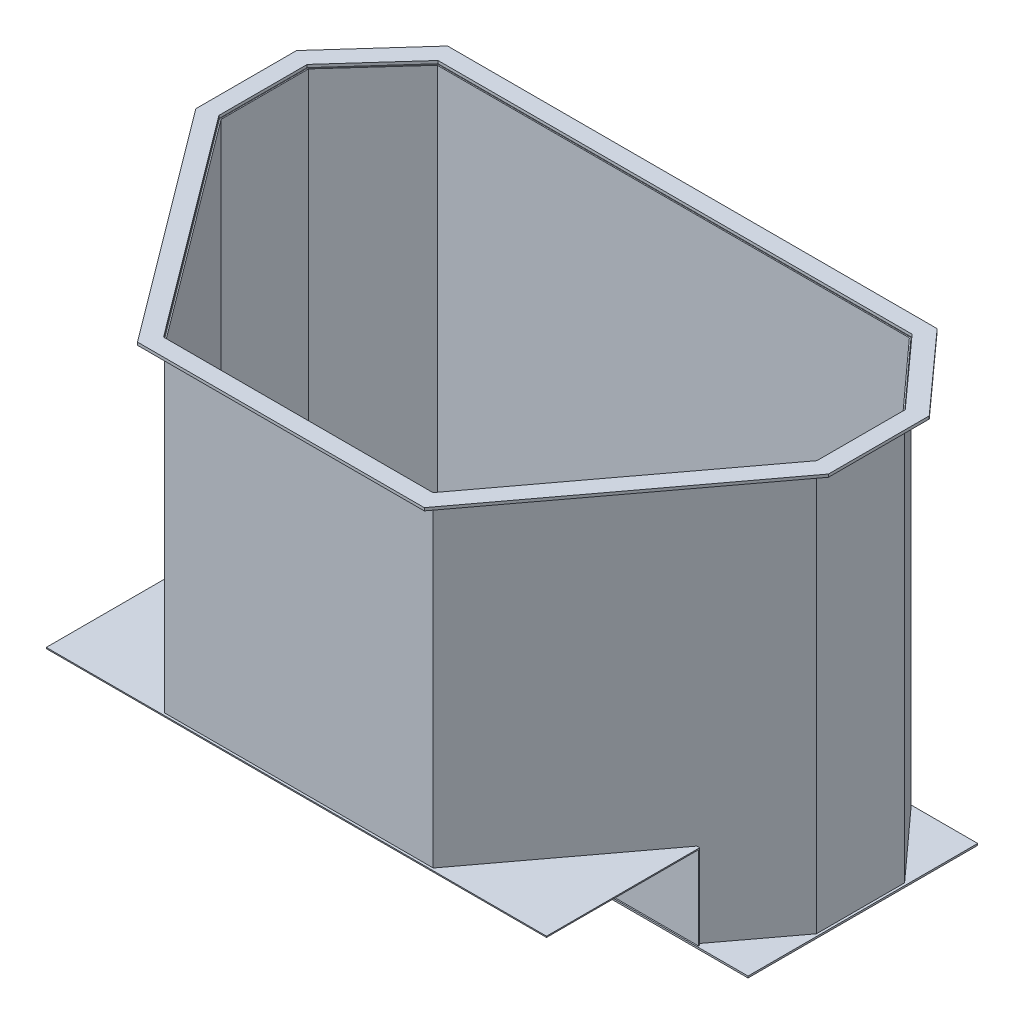
SolidWorks part; units mm, degrees
ref_plane "Front Plane" through (0, 0, 0) normal (0, 0, 1) x (1, 0, 0)
ref_plane "Top Plane" through (0, 0, 0) normal (0, 1, 0) x (1, 0, 0)
ref_plane "Right Plane" through (0, 0, 0) normal (1, 0, 0) x (0, 0, -1)
sketch "Sketch1" plane through (0, 0, 0) normal (0, 1, 0) x (1, 0, 0)
  line L0 (-5428.3271, 0) -> (7958.8254, 0) construction
  line L1 (0, -4061.0417) -> (0, 5407.9198) construction
  line L2 (-1675, 790) -> (1675, 790)
  line L3 (-950, -1860) -> (950, -1860)
  line L4 (-2110, 310) -> (-2110, -310)
  line L5 (2110, 310) -> (2110, -310)
  line L6 (-1661.4236, -790) -> (2260.7464, -790) construction
  line L7 (-1675, 790) -> (-2110, 310)
  line L8 (1675, 790) -> (2110, 310)
  line L9 (-950, -1860) -> (-2110, -310)
  line L10 (2110, -310) -> (950, -1860)
  line L11 (-1678.5464, 798) -> (1678.5464, 798)
  line L12 (1678.5464, 798) -> (2118, 313.0857)
  line L13 (2118, 313.0857) -> (2118, -312.6621)
  line L14 (2118, -312.6621) -> (954.0052, -1868)
  line L15 (-954.0052, -1868) -> (954.0052, -1868)
  line L16 (-954.0052, -1868) -> (-2118, -312.6621)
  line L17 (-2118, 313.0857) -> (-2118, -312.6621)
  line L18 (-1678.5464, 798) -> (-2118, 313.0857)
  dimension "D1" = 790
  dimension "D2" = 790
  dimension "D3" = 1070
  dimension "D4" = 2110
  dimension "D5" = 2110
  dimension "D6" = 1900
  dimension "D7" = 950
  dimension "D8" = 435
  dimension "D9" = 480
  dimension "D10" = 435
  dimension "D11" = 480
  dimension "D12" = 1160
  dimension "D13" = 1160
  dimension "D14" = 1550
  dimension "D15" = 1550
  dimension "D16" = 1936.001
  dimension "D17" = 1936.001
  dimension "D18" = 8
  dimension "D19" = 3357.0928
  dimension "D20" = 625.7478
  dimension "D21" = 1942.6683
  dimension "D22" = 1908.0103
  dimension "D23" = 654.4168
  dimension "D24" = 647.7847
extrude "Boss-Extrude1" add sketch "Sketch1" along normal blind 2890
sketch "Sketch2" plane through (0, 0, 0) normal (0, -1, 0) x (1, 0, 0)
  line L0 (0, 4061.0417) -> (0, -5407.9198) construction
  line L1 (-2135, 815) -> (2135, 815)
  line L2 (-2135, 815) -> (-2135, -815)
  line L3 (-2135, -815) -> (2135, -815)
  line L4 (2135, 815) -> (2135, -815)
  line L7 (-5428.3271, 0) -> (7958.8254, 0) construction
  dimension "D1" = 4270
  dimension "D2" = 2135
  dimension "D3" = 1630
  dimension "D4" = 815
extrude "Boss-Extrude2" add sketch "Sketch2" along normal blind 12
sketch "Sketch3" plane through (0, 0, 0) normal (0, -1, 0) x (1, 0, 0)
  line L1 (-1758.2001, 1998.1832) -> (1908.3596, 1998.1832)
  line L2 (-1758.2001, 1998.1832) -> (-1758.2001, 798)
  line L3 (-1758.2001, 798) -> (1908.3596, 798)
  line L4 (1908.3596, 1998.1832) -> (1908.3596, 798)
  line L5 (-5428.3271, 0) -> (7958.8254, 0) construction
  dimension "D1" = 798
extrude "Cut-Extrude1" cut sketch "Sketch3" against normal blind 600
sketch "Sketch4" plane through (0, 0, 0) normal (1, 0, 0) x (0, 0, -1)
  line L0 (-806, 592) -> (-806, 0)
  line L1 (-1885, 600) -> (-798, 600)
  line L2 (-1885, 600) -> (-1885, 592)
  line L3 (-1885, 592) -> (-806, 592)
  line L7 (-806, 0) -> (-798, 0)
  line L8 (-798, 600) -> (-798, 0)
  line L9 (-1868, 0) -> (-312.6621, 0) construction
  line L10 (-1868, 2890) -> (-1868, 600) construction
  dimension "D1" = 798
  dimension "D2" = 0
  dimension "D3" = 17
  dimension "D4" = 600
  dimension "D5" = 8
  dimension "D6" = 8
  dimension "D7" = 8
extrude "Boss-Extrude3" add sketch "Sketch4" along normal mid plane 3550
sketch "Sketch5" plane through (0, 2890, 0) normal (0, 1, 0) x (1, 0, 0)
  line L0 (-1737, 925) -> (1737, 925)
  line L1 (-1017.5, -1995) -> (1017.5, -1995)
  line L2 (2245, 361) -> (2245, -354)
  line L3 (-2245, 361) -> (-2245, -354)
  line L4 (-5428.3271, 0) -> (7958.8254, 0) construction
  line L5 (0, -4061.0417) -> (0, 5407.9198) construction
  line L6 (-2245, -354) -> (-1017.5, -1995)
  line L7 (1017.5, -1995) -> (2245, -354)
  line L8 (2245, 361) -> (1737, 925)
  line L9 (-1737, 925) -> (-2245, 361)
  line L10 (-1682.2493, 802) -> (1682.2493, 802)
  line L11 (2122, 313.7728) -> (1682.2493, 802)
  line L12 (2122, 313.7728) -> (2122, -313.0867)
  line L13 (955.9024, -1872) -> (2122, -313.0867)
  line L14 (-955.9024, -1872) -> (955.9024, -1872)
  line L15 (-2122, -313.0867) -> (-955.9024, -1872)
  line L16 (-2122, 313.7728) -> (-2122, -313.0867)
  line L17 (-1682.2493, 802) -> (-2122, 313.7728)
  dimension "D1" = 925
  dimension "D2" = 1995
  dimension "D3" = 2920
  dimension "D4" = 3474
  dimension "D5" = 1737
  dimension "D6" = 2035
  dimension "D7" = 1017.5
  dimension "D8" = 508
  dimension "D9" = 564
  dimension "D10" = 715
  dimension "D11" = 715
  dimension "D12" = 508
  dimension "D13" = 564
  dimension "D14" = 1227.5
  dimension "D15" = 1227.5
  dimension "D16" = 1641
  dimension "D17" = 1641
  dimension "D19" = 4490
  dimension "D18" = 123
extrude "Boss-Extrude4" add sketch "Sketch5" along normal blind 20 separate body
